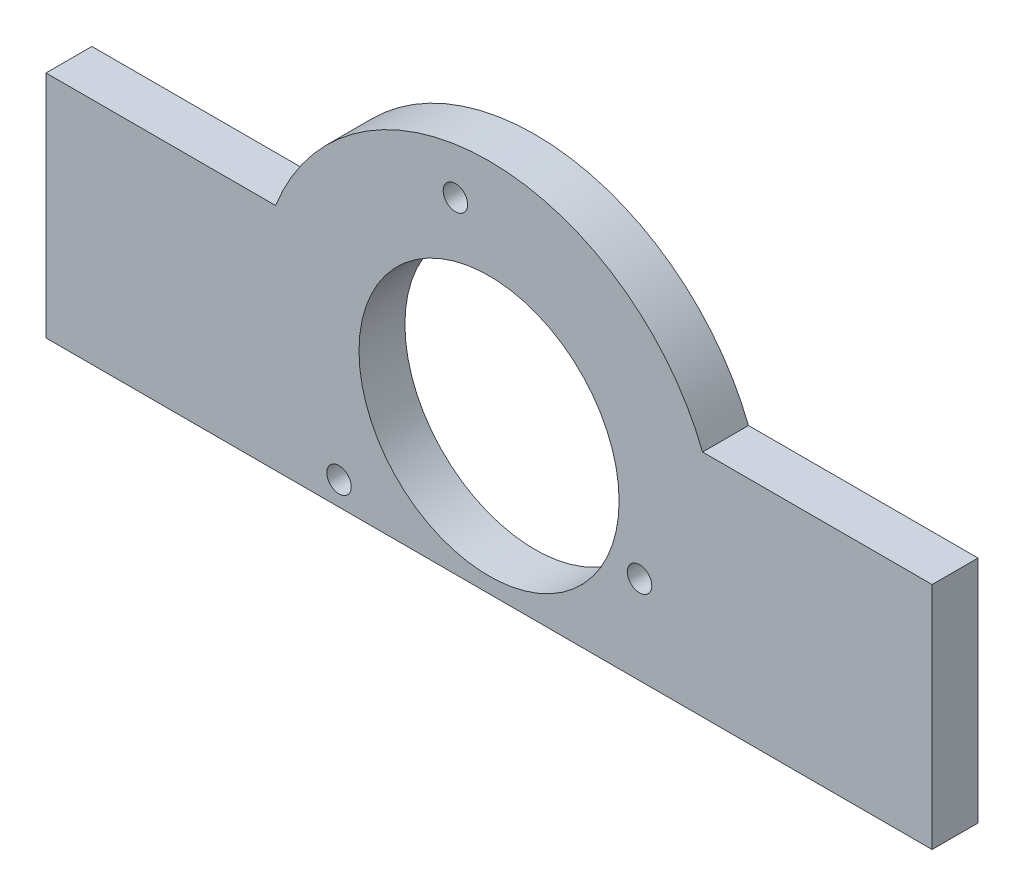
SolidWorks part; units mm, degrees
ref_plane "Front Plane" through (0, 0, 0) normal (0, 0, 1) x (1, 0, 0)
ref_plane "Top Plane" through (0, 0, 0) normal (0, 1, 0) x (1, 0, 0)
ref_plane "Right Plane" through (0, 0, 0) normal (1, 0, 0) x (0, 0, -1)
sketch "Sketch1" plane through (0, 0, 0) normal (0, 0, 1) x (1, 0, 0)
  circle A0 centre (0, 0) radius 38.1
  circle A1 centre (0, 0) radius 21.59
  dimension "D1" = 76.2
  dimension "D2" = 43.18
extrude "Boss-Extrude1" add sketch "Sketch1" along normal blind 7.62
sketch "Sketch2" plane through (0, 0, 7.62) normal (0, 0, 1) x (1, 0, 0)
  line L0 (0, 0) -> (0, -38.1) construction
  line L6 (0, -38.1) -> (-36.2561, -38.1)
  line L7 (-36.2561, -38.1) -> (-36.2561, -24.13)
  line L8 (-36.2561, -24.13) -> (33.7504, -24.13)
  line L9 (33.7504, -24.13) -> (33.7504, -38.1)
  line L10 (33.7504, -38.1) -> (0, -38.1)
  circle A0 centre (0, 0) radius 38.1 construction
  dimension "D1" = 13.97
extrude "Cut-Extrude1" cut sketch "Sketch2" against normal through all
sketch "Sketch7" plane through (0, 0, 7.62) normal (0, 0, 1) x (1, 0, 0)
  line L0 (-5.5817, 30.0374) -> (-24.9028, -20.1911) construction
  line L1 (-5.5817, 30.0374) -> (24.9828, -9.4847) construction
  line L2 (24.9828, -9.4847) -> (-24.9028, -20.1911) construction
  circle A0 centre (-24.9028, -20.1911) radius 2.032
  circle A1 centre (-5.5817, 30.0374) radius 2.032
  circle A2 centre (24.9828, -9.4847) radius 2.032
  dimension "D1" = 4.064
  dimension "D2" = 50.2285
  dimension "D3" = 49.9618
  dimension "D4" = 49.8856
extrude "Cut-Extrude2" cut sketch "Sketch7" against normal through all
sketch "Sketch9" plane through (0, 0, 7.62) normal (0, 0, 1) x (1, 0, 0)
  line L0 (-29.4848, -24.13) -> (-73.5464, -24.13)
  line L1 (-73.5464, -24.13) -> (-73.5464, 13.97)
  line L2 (-73.5464, 13.97) -> (-35.4464, 13.97)
  line L3 (-35.4464, 13.97) -> (-29.4848, -24.13)
  line L4 (29.4848, -24.13) -> (73.5464, -24.13)
  line L5 (73.5464, -24.13) -> (73.5464, 13.97)
  line L6 (73.5464, 13.97) -> (35.4464, 13.97)
  line L7 (35.4464, 13.97) -> (29.4848, -24.13)
  arc A0 (29.4848, -24.13) -> (-29.4848, -24.13) centre (0, 0) ccw construction
  dimension "D1" = 38.1
  dimension "D2" = 38.1
extrude "Boss-Extrude2" add sketch "Sketch9" along normal blind 7.62 from surface at -7.62 starting at face at (-22.8708, -20.1911, 0)
equation "\"Foamcore\" = .1in"
equation "\"MDF\" = .3in"
equation "\"Gmaterial\"= \"MDF\""
equation "\"PVC-ID\" = \"1.590in\""
equation "\"PVC-OD\" = \"1.900in\""
equation "\"PVC-Sleeve-Width\" = \".51in\""
equation "\"D1@Boss-Extrude1\"=\"Gmaterial\""
equation "\"D1@Boss-Extrude2\"=\"Gmaterial\""
equation "\"D2@Boss-Extrude2\"=\"Gmaterial\""
